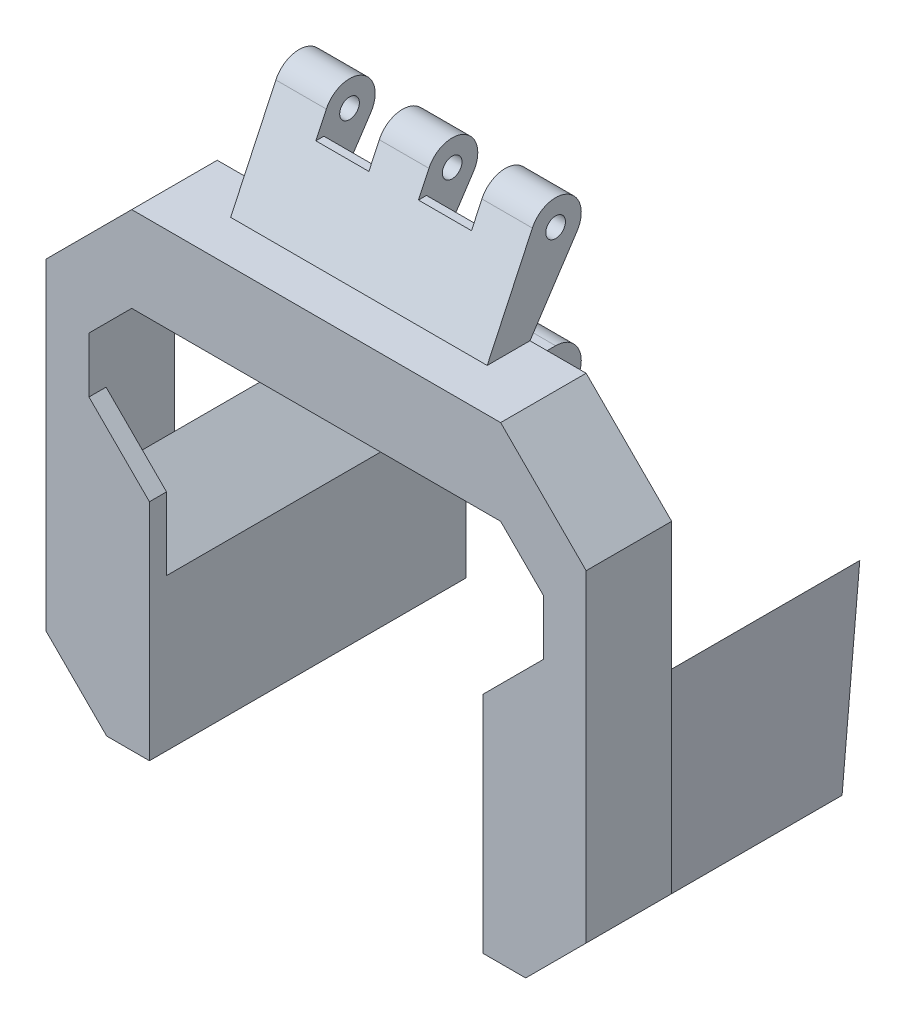
SolidWorks part; units mm, degrees
ref_plane "前视基准面" through (0, 0, 0) normal (0, 0, 1) x (1, 0, 0)
ref_plane "上视基准面" through (0, 0, 0) normal (0, 1, 0) x (1, 0, 0)
ref_plane "右视基准面" through (0, 0, 0) normal (1, 0, 0) x (0, 0, -1)
other "Configuration Table"
sketch "草图1" plane through (0, 0, 0) normal (0, 0, 1) x (1, 0, 0)
  line L0 (0, 0) -> (0, -349093.2642) construction
  line L1 (-19.5, 14.7145) -> (-19.5, -3.0355)
  line L2 (-19.5, -3.0355) -> (-24.5, -3.0355)
  line L3 (-24.5, -3.0355) -> (-31.5711, 4.0355)
  line L4 (-31.5711, 41.75) -> (-21.5711, 51.75)
  line L5 (-19.5, 14.7145) -> (-26.5711, 21.7855)
  line L6 (-26.5711, 21.7855) -> (-26.5711, 36.75)
  line L7 (-21.5711, 41.75) -> (21.5711, 41.75)
  line L8 (-19, 17.75) -> (-26.0732, 24.8232)
  line L9 (-19, 17.75) -> (19, 17.75)
  line L10 (-19, 17.75) -> (-19, -17.75)
  line L11 (-19, -17.75) -> (19, -17.75)
  line L12 (19, 17.75) -> (19, -17.75)
  line L13 (-19, 17.75) -> (19, -17.75) construction
  line L14 (-19, -17.75) -> (19, 17.75) construction
  line L15 (-17.9393, 18.8107) -> (-25.0125, 25.8838)
  line L16 (-20.0607, 16.6893) -> (-27.1338, 23.7625)
  line L17 (-31.5711, 4.0355) -> (-31.5711, 41.75)
  line L18 (-26.5711, 36.75) -> (-21.5711, 41.75)
  line L19 (-21.5711, 51.75) -> (21.5711, 51.75)
  line L20 (31.5711, 41.75) -> (21.5711, 51.75)
  line L21 (26.5711, 36.75) -> (21.5711, 41.75)
  line L22 (26.5711, 21.7855) -> (26.5711, 36.75)
  line L23 (31.5711, 4.0355) -> (31.5711, 41.75)
  line L24 (24.5, -3.0355) -> (31.5711, 4.0355)
  line L25 (19.5, 14.7145) -> (26.5711, 21.7855)
  line L26 (19.5, 14.7145) -> (19.5, -3.0355)
  line L27 (19.5, -3.0355) -> (24.5, -3.0355)
  point P9 (0, 0)
  point P10 (-26.5711, 41.75)
  point P22 (-31.5711, 51.75)
  point P29 (0, 41.75)
  point P30 (0, 51.75)
  dimension "D1" = 39
  dimension "D2" = 35.5
  dimension "D3" = 38
  dimension "D4" = 17.75
  dimension "D5" = 36
  dimension "D8" = 10
  dimension "D9" = 1
  dimension "D10" = 5
  dimension "D11" = 5
  dimension "D12" = 24
  dimension "D13" = 10
  dimension "D15" = 45
  dimension "D6" = 1.5
  dimension "D7" = 1.5
extrude "凸台-拉伸1" add sketch "草图1" along normal blind 25 contours L26 L27 L24 L23 L20 L19 L4 L17 L3 L2 L1 L5 L6 L18 L7 L21 L22 L25
sketch "草图2" plane through (0, 0, 25) normal (0, 0, 1) x (1, 0, 0)
  line L19 (-26.5711, 30.2708) -> (-19.5, 23.1997)
  line L20 (-19.5, 23.1997) -> (-19.5, 14.7145)
  line L21 (0, 0) -> (0, -50000) construction
  line L22 (-26.5711, 21.7855) -> (-19.5, 14.7145)
  line L23 (-19.5, 14.7145) -> (-26.5711, 21.7855) construction
  line L24 (-26.5711, 21.7855) -> (-26.5711, 36.75) construction
  line L25 (-26.5711, 30.2708) -> (-26.5711, 21.7855)
  line L26 (26.5711, 30.2708) -> (19.5, 23.1997)
  line L27 (19.5, 23.1997) -> (19.5, 14.7145)
  line L28 (26.5711, 21.7855) -> (19.5, 14.7145)
  line L29 (26.5711, 30.2708) -> (26.5711, 21.7855)
  dimension "D1" = 6
extrude "凸台-拉伸2" add sketch "草图2" against normal blind 2
sketch "草图3" plane through (0, 0, 0) normal (0, 0, -1) x (-1, 0, 0)
  line L0 (-26.5711, 21.7855) -> (-24.5, -3.0355)
  line L1 (26.5711, 21.7855) -> (24.5, -3.0355)
  line L18 (-19.5, -3.0355) -> (-19.5, 14.7145)
  line L19 (-19.5, 14.7145) -> (-26.5711, 21.7855)
  line L20 (-26.5711, 21.7855) -> (-26.5711, 36.75)
  line L21 (-26.5711, 36.75) -> (-21.5711, 41.75)
  line L22 (-21.5711, 41.75) -> (21.5711, 41.75)
  line L23 (21.5711, 41.75) -> (26.5711, 36.75)
  line L24 (26.5711, 36.75) -> (26.5711, 21.7855)
  line L25 (26.5711, 21.7855) -> (19.5, 14.7145)
  line L26 (19.5, 14.7145) -> (19.5, -3.0355)
  line L27 (19.5, -3.0355) -> (24.5, -3.0355)
  line L28 (24.5, -3.0355) -> (31.5711, 4.0355)
  line L29 (31.5711, 4.0355) -> (31.5711, 41.75)
  line L30 (31.5711, 41.75) -> (21.5711, 51.75)
  line L31 (21.5711, 51.75) -> (-21.5711, 51.75)
  line L32 (-21.5711, 51.75) -> (-31.5711, 41.75)
  line L33 (-31.5711, 41.75) -> (-31.5711, 4.0355)
  line L34 (-31.5711, 4.0355) -> (-24.5, -3.0355)
  line L35 (-24.5, -3.0355) -> (-19.5, -3.0355)
  line L36 (-19.5, -3.0355) -> (-19.5, 14.7145)
  line L37 (-19.5, 14.7145) -> (-26.5711, 21.7855)
  line L38 (-26.5711, 21.7855) -> (-26.5711, 36.75)
  line L39 (-26.5711, 36.75) -> (-21.5711, 41.75)
  line L40 (-21.5711, 41.75) -> (21.5711, 41.75)
  line L41 (21.5711, 41.75) -> (26.5711, 36.75)
  line L42 (26.5711, 36.75) -> (26.5711, 21.7855)
  line L43 (26.5711, 21.7855) -> (19.5, 14.7145)
  line L44 (19.5, 14.7145) -> (19.5, -3.0355)
  line L45 (19.5, -3.0355) -> (24.5, -3.0355)
  line L46 (24.5, -3.0355) -> (31.5711, 4.0355)
  line L47 (31.5711, 4.0355) -> (31.5711, 41.75)
  line L48 (31.5711, 41.75) -> (21.5711, 51.75)
  line L49 (21.5711, 51.75) -> (-21.5711, 51.75)
  line L50 (-21.5711, 51.75) -> (-31.5711, 41.75)
  line L51 (-31.5711, 41.75) -> (-31.5711, 4.0355)
  line L52 (-31.5711, 4.0355) -> (-24.5, -3.0355)
  line L53 (-24.5, -3.0355) -> (-19.5, -3.0355)
  line M21 (-26.5711, 21.7855) -> (-26.5711, 36.75)
  line M22 (-26.5711, 36.75) -> (-21.5711, 41.75)
  line M23 (-21.5711, 41.75) -> (21.5711, 41.75)
  line M24 (21.5711, 41.75) -> (26.5711, 36.75)
  line M25 (26.5711, 36.75) -> (26.5711, 21.7855)
  line M29 (24.5, -3.0355) -> (31.5711, 4.0355)
  line M30 (31.5711, 4.0355) -> (31.5711, 41.75)
  line M31 (31.5711, 41.75) -> (21.5711, 51.75)
  line M32 (21.5711, 51.75) -> (-21.5711, 51.75)
  line M33 (-21.5711, 51.75) -> (-31.5711, 41.75)
  line M34 (-31.5711, 41.75) -> (-31.5711, 4.0355)
  line M35 (-31.5711, 4.0355) -> (-24.5, -3.0355)
  dimension "D1" = 0
extrude "切除-拉伸1" cut sketch "草图3" against normal blind 15 contours L1 L0 M25 M29 M30 M31 M32 M33 M34 M35 M21 M22 M23 M24
sketch "草图4" plane through (0, 0, 0) normal (1, 0, 0) x (0, 0, -1)
  line L0 (-15, 46.75) -> (-12, 46.75) construction
  line L1 (-15, 51.75) -> (-15, 41.75) construction
  line L2 (-15, 49.75) -> (-12, 49.75)
  line L3 (-15, 43.75) -> (-12, 43.75)
  line L4 (-15, 61.75) -> (-12, 61.75) construction
  line L5 (-15, 64.75) -> (-12, 64.75)
  line L6 (-15, 58.75) -> (-12, 58.75)
  line L7 (-12, 46.75) -> (-12, 61.75) construction
  line L8 (-15, 51.75) -> (-15, 58.75)
  line L9 (-20, 51.75) -> (-20, 59.75)
  line L10 (-25, 51.75) -> (-15, 51.75) construction
  line L11 (-20, 59.75) -> (-15, 64.75)
  line L12 (-20, 51.75) -> (-15, 51.75)
  line L13 (-14.7164, 63.0232) -> (-20, 51.75)
  line L14 (-9.4954, 60.0986) -> (-15, 51.75)
  arc A0 (-15, 49.75) -> (-15, 43.75) centre (-15, 46.75) ccw
  arc A1 (-12, 43.75) -> (-12, 49.75) centre (-12, 46.75) ccw
  circle A2 centre (-12, 46.75) radius 1.15
  circle A3 centre (-12, 61.75) radius 1.15
  arc A4 (-15, 64.75) -> (-15, 58.75) centre (-15, 61.75) ccw
  arc A5 (-12, 58.75) -> (-12, 64.75) centre (-12, 61.75) ccw
  circle A6 centre (-12, 61.75) radius 3
  point P4 (-13.5, 46.75)
  point P14 (-13.5, 61.75)
  dimension "D1" = 2.3
  dimension "D2" = 3
  dimension "D3" = 3
  dimension "D5" = 15
  dimension "D6" = 45
  dimension "D4" = 2
extrude "凸台-拉伸3" add sketch "草图4" along normal mid plane 30 contours A5 A6 A3 | A6 L13 A4 L6 | A4 L13 L9 L12 L8 | A5 L6 L8 L14 | L3 A1 L2 A0 A2
sketch "草图5" plane through (0, 0, 15) normal (0, 0, -1) x (-1, 0, 0)
  line L0 (0, 44.75) -> (0, -49955.25) construction
  line L3 (-9.1, 65.75) -> (-2.9, 65.75)
  line L4 (-9.1, 65.75) -> (-9.1, 43.75)
  line L5 (-9.1, 43.75) -> (-2.9, 43.75)
  line L6 (-2.9, 65.75) -> (-2.9, 43.75)
  line L7 (-9.1, 65.75) -> (-2.9, 43.75) construction
  line L8 (-9.1, 43.75) -> (-2.9, 65.75) construction
  line L9 (-15, 49.75) -> (-15, 43.75) construction
  line L10 (9.1, 43.75) -> (2.9, 43.75)
  line L11 (2.9, 65.75) -> (2.9, 43.75)
  line L12 (9.1, 65.75) -> (2.9, 65.75)
  line L13 (9.1, 65.75) -> (9.1, 43.75)
  line L14 (-15, 49.75) -> (-15, 43.75) construction
  line L15 (-15, 43.75) -> (15, 43.75) construction
  point P5 (-6, 54.75)
  dimension "D1" = 6.2
  dimension "D2" = 5.9
  dimension "D3" = 22
  dimension "D4" = 15
extrude "切除-拉伸2" cut sketch "草图5" along normal through all
sketch "草图6" plane through (0, 0, 15) normal (0, 0, -1) x (-1, 0, 0)
  line L0 (-2.9, 51.75) -> (-2.9, 62.4182) construction
  line L1 (-9.1, 62.4182) -> (-2.9, 62.4182)
  line L2 (-9.1, 62.4182) -> (-9.1, 60.4182)
  line L3 (-9.1, 60.4182) -> (-2.9, 60.4182)
  line L4 (-2.9, 62.4182) -> (-2.9, 60.4182)
  line L5 (9.1, 51.75) -> (9.1, 62.4182) construction
  line L6 (2.9, 62.4182) -> (9.1, 62.4182)
  line L7 (2.9, 62.4182) -> (2.9, 60.4182)
  line L8 (2.9, 60.4182) -> (9.1, 60.4182)
  line L9 (9.1, 62.4182) -> (9.1, 60.4182)
  dimension "D1" = 2
extrude "切除-拉伸3" cut sketch "草图6" against normal through all
sketch "草图7" plane through (0, 0, 0) normal (0, 0, -1) x (-1, 0, 0)
  line L4 (-26.5711, 21.7855) -> (-24.5, -3.0355)
  line L5 (-24.5, -3.0355) -> (-19.5, -3.0355)
  line L6 (-19.5, -3.0355) -> (-19.5, 14.7145)
  line L7 (-19.5, 14.7145) -> (-26.5711, 21.7855)
  line L8 (-26.5711, 21.7855) -> (-24.5, -3.0355)
  line L9 (-24.5, -3.0355) -> (-19.5, -3.0355)
  line L10 (-19.5, -3.0355) -> (-19.5, 14.7145)
  line L11 (-19.5, 14.7145) -> (-26.5711, 21.7855)
  dimension "D1" = 0
extrude "凸台-拉伸4" add sketch "草图7" along normal blind 12
sketch "草图8" plane through (0, 0, 0) normal (0, 0, -1) x (-1, 0, 0)
  line L4 (19.5, -3.0355) -> (24.5, -3.0355)
  line L5 (24.5, -3.0355) -> (26.5711, 21.7855)
  line L6 (26.5711, 21.7855) -> (19.5, 14.7145)
  line L7 (19.5, 14.7145) -> (19.5, -3.0355)
  line L8 (19.5, -3.0355) -> (24.5, -3.0355)
  line L9 (24.5, -3.0355) -> (26.5711, 21.7855)
  line L10 (26.5711, 21.7855) -> (19.5, 14.7145)
  line L11 (19.5, 14.7145) -> (19.5, -3.0355)
  dimension "D1" = 0
extrude "凸台-拉伸5" add sketch "草图8" along normal blind 12
